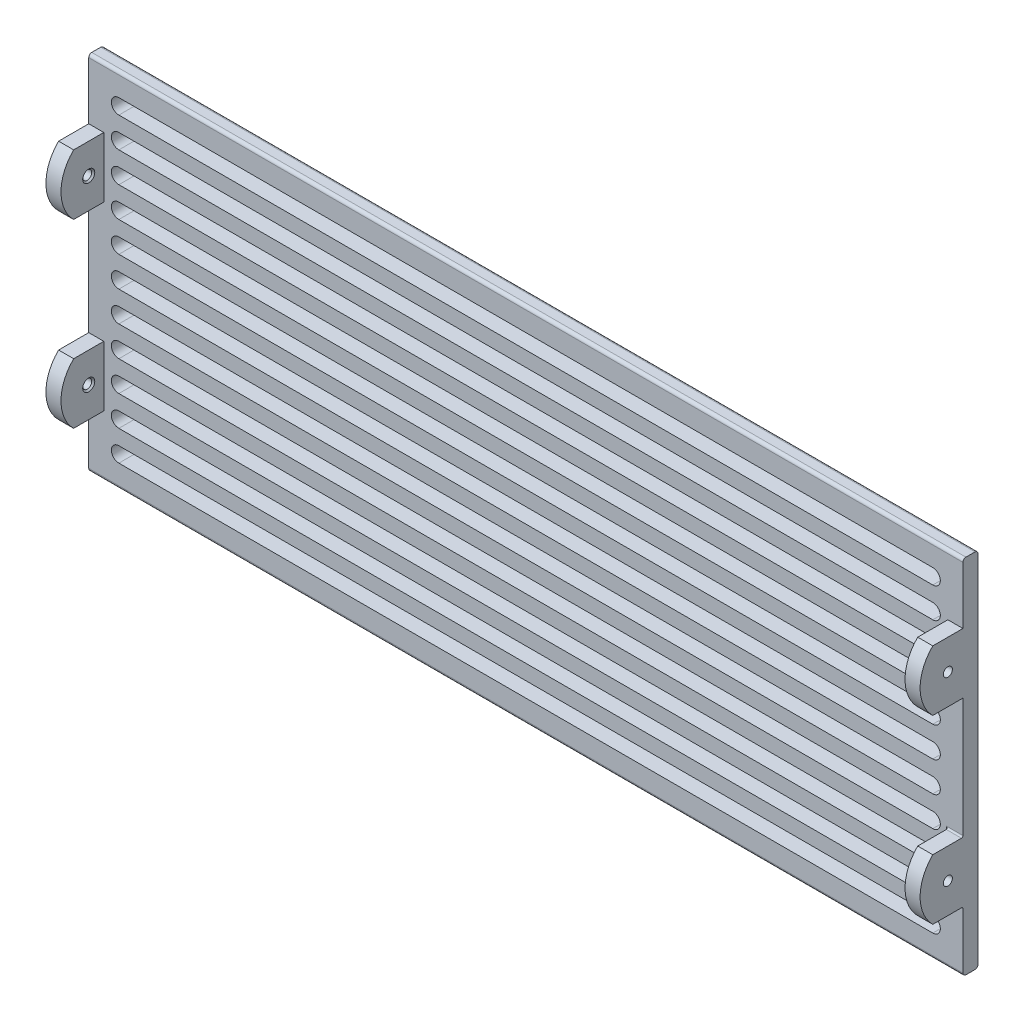
SolidWorks part; units mm, degrees
ref_plane "Plan de face" through (0, 0, 0) normal (0, 0, 1) x (1, 0, 0)
ref_plane "Plan de dessus" through (0, 0, 0) normal (0, 1, 0) x (1, 0, 0)
ref_plane "Plan de droite" through (0, 0, 0) normal (1, 0, 0) x (0, 0, -1)
sketch "Esquisse1" plane through (0, 0, 0) normal (0, 0, 1) x (1, 0, 0)
  line L0 (-135, 0) -> (135, 0) construction
  line L1 (-145, 60) -> (145, 60)
  line L2 (-145, 60) -> (-145, -60)
  line L3 (-145, -60) -> (145, -60)
  line L4 (145, 60) -> (145, -60)
  line L5 (-145, 60) -> (145, -60) construction
  line L6 (-145, -60) -> (145, 60) construction
  line L7 (-135, 2.5) -> (135, 2.5)
  line L8 (-135, -2.5) -> (135, -2.5)
  line L9 (-135, 7.5) -> (135, 7.5)
  line L10 (-135, 12.5) -> (135, 12.5)
  line L11 (-135, 10) -> (135, 10) construction
  line L12 (-135, 17.5) -> (135, 17.5)
  line L13 (-135, 22.5) -> (135, 22.5)
  line L14 (-135, 20) -> (135, 20) construction
  line L15 (-135, 27.5) -> (135, 27.5)
  line L16 (-135, 32.5) -> (135, 32.5)
  line L17 (-135, 30) -> (135, 30) construction
  line L18 (-135, 37.5) -> (135, 37.5)
  line L19 (-135, 42.5) -> (135, 42.5)
  line L20 (-135, 40) -> (135, 40) construction
  line L21 (-135, 47.5) -> (135, 47.5)
  line L22 (-135, 52.5) -> (135, 52.5)
  line L23 (-135, 50) -> (135, 50) construction
  line L24 (-135, -12.5) -> (135, -12.5)
  line L25 (-135, -7.5) -> (135, -7.5)
  line L26 (-135, -10) -> (135, -10) construction
  line L27 (-135, -22.5) -> (135, -22.5)
  line L28 (-135, -17.5) -> (135, -17.5)
  line L29 (-135, -20) -> (135, -20) construction
  line L30 (-135, -32.5) -> (135, -32.5)
  line L31 (-135, -27.5) -> (135, -27.5)
  line L32 (-135, -30) -> (135, -30) construction
  line L33 (-135, -42.5) -> (135, -42.5)
  line L34 (-135, -37.5) -> (135, -37.5)
  line L35 (-135, -40) -> (135, -40) construction
  line L36 (-135, -52.5) -> (135, -52.5)
  line L37 (-135, -47.5) -> (135, -47.5)
  line L38 (-135, -50) -> (135, -50) construction
  arc A0 (-135, 2.5) -> (-135, -2.5) centre (-135, 0) ccw
  arc A1 (135, -2.5) -> (135, 2.5) centre (135, 0) ccw
  arc A2 (-135, 12.5) -> (-135, 7.5) centre (-135, 10) ccw
  arc A3 (135, 7.5) -> (135, 12.5) centre (135, 10) ccw
  arc A4 (-135, 22.5) -> (-135, 17.5) centre (-135, 20) ccw
  arc A5 (135, 17.5) -> (135, 22.5) centre (135, 20) ccw
  arc A6 (-135, 32.5) -> (-135, 27.5) centre (-135, 30) ccw
  arc A7 (135, 27.5) -> (135, 32.5) centre (135, 30) ccw
  arc A8 (-135, 42.5) -> (-135, 37.5) centre (-135, 40) ccw
  arc A9 (135, 37.5) -> (135, 42.5) centre (135, 40) ccw
  arc A10 (-135, 52.5) -> (-135, 47.5) centre (-135, 50) ccw
  arc A11 (135, 47.5) -> (135, 52.5) centre (135, 50) ccw
  arc A12 (-135, -7.5) -> (-135, -12.5) centre (-135, -10) ccw
  arc A13 (135, -12.5) -> (135, -7.5) centre (135, -10) ccw
  arc A14 (-135, -17.5) -> (-135, -22.5) centre (-135, -20) ccw
  arc A15 (135, -22.5) -> (135, -17.5) centre (135, -20) ccw
  arc A16 (-135, -27.5) -> (-135, -32.5) centre (-135, -30) ccw
  arc A17 (135, -32.5) -> (135, -27.5) centre (135, -30) ccw
  arc A18 (-135, -37.5) -> (-135, -42.5) centre (-135, -40) ccw
  arc A19 (135, -42.5) -> (135, -37.5) centre (135, -40) ccw
  arc A20 (-135, -47.5) -> (-135, -52.5) centre (-135, -50) ccw
  arc A21 (135, -52.5) -> (135, -47.5) centre (135, -50) ccw
  point P0 (0, 0)
  point P8 (0, 0)
  point P16 (0, 10)
  point P23 (0, 20)
  point P30 (0, 30)
  point P37 (0, 40)
  point P44 (0, 50)
  point P51 (0, -10)
  point P58 (0, -20)
  point P65 (0, -30)
  point P72 (0, -40)
  point P79 (0, -50)
  dimension "D1" = 120
  dimension "D2" = 290
  dimension "D3" = 5
  dimension "D4" = 270
  dimension "D5" = 6
  dimension "D6" = 6
extrude "Boss.-Extru.1" add sketch "Esquisse1" along normal blind 5
fillet "Congé1" radius 1 2 edges at (0, -60, 0) (0, -60, 5)
fillet "Congé2" radius 1 2 edges at (0, 60, 0) (0, 60, 5)
sketch "Esquisse2" plane through (145, 0, 0) normal (1, 0, 0) x (0, 0, -1)
  line L0 (-58.0049, 0) -> (46.4506, 0) construction
  line L1 (-5, -59) -> (-5, 59) construction
  line L2 (-5, 20) -> (-15, 20)
  line L3 (-5, 20) -> (-5, 40)
  line L4 (-5, 40) -> (-15, 40)
  line L6 (-5, -20) -> (-5, -40)
  line L7 (-5, -40) -> (-15, -40)
  line L8 (-5, -20) -> (-15, -20)
  circle A0 centre (-10, 30) radius 1.5
  arc A1 (-15, 40) -> (-15, 20) centre (-5.202, 30) ccw
  circle A2 centre (-10, -30) radius 1.5
  arc A3 (-15, -40) -> (-15, -20) centre (-5.202, -30) cw
  dimension "D4" = 3
  dimension "D1" = 20
  dimension "D5" = 14
  dimension "D2" = 20
  dimension "D3" = 10
extrude "Boss.-Extru.2" add sketch "Esquisse2" against normal blind 5
mirror "Symétrie1" about plane through (0, 0, 0) normal (1, 0, 0) of "Boss.-Extru.2"
fillet "Congé3" radius 0.5 3 edges at (140, -30, 5) (142.5, -20, 5) (142.5, -40, 5)
chamfer "Chanfrein1" distance 0.5 angle 45 4 edges at (140, 31.5, 10) (140, -31.5, 10) (-140, -31.5, 10) (-140, 31.5, 10)
